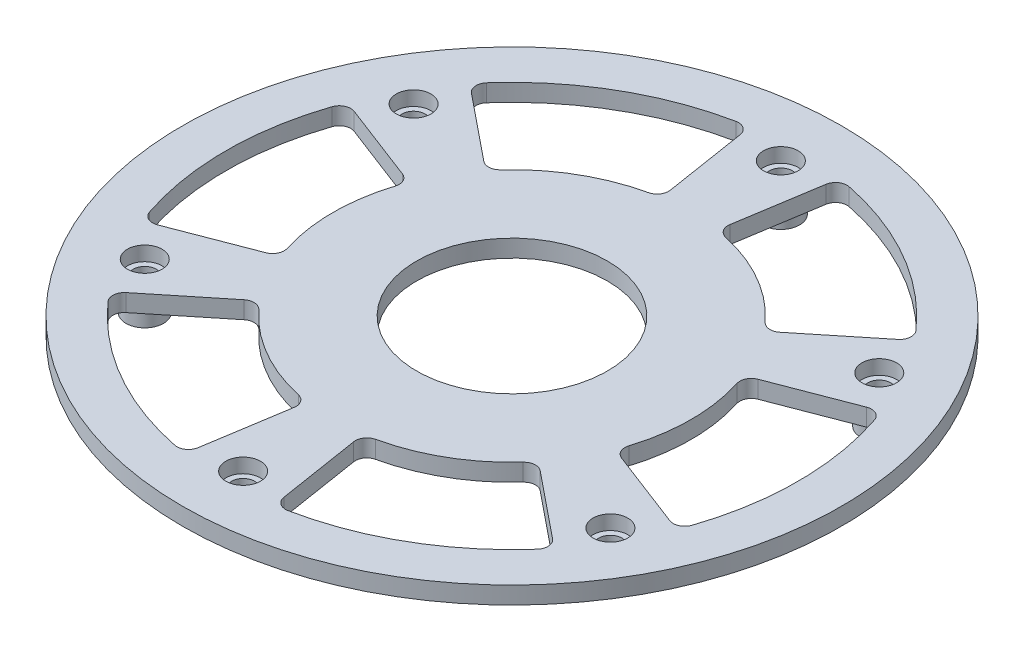
SolidWorks part; units mm, degrees
ref_plane "Front Plane" through (0, 0, 0) normal (0, 0, 1) x (1, 0, 0)
ref_plane "Top Plane" through (0, 0, 0) normal (0, 1, 0) x (1, 0, 0)
ref_plane "Right Plane" through (0, 0, 0) normal (1, 0, 0) x (0, 0, -1)
sketch "Sketch1" plane through (0, 0, 0) normal (0, 1, 0) x (1, 0, 0)
  circle A0 centre (0, 0) radius 57
  dimension "D1" = 114
extrude "Boss-Extrude1" add sketch "Sketch1" along normal blind 3
sketch "Sketch2" plane through (0, 3, 0) normal (0, 1, 0) x (1, 0, 0)
  line L0 (0, 62.5097) -> (0, -64.2706) construction
  circle A0 centre (0, 46.5) radius 2
  dimension "D1" = 4
  dimension "D2" = 46.5
extrude "Cut-Extrude1" cut sketch "Sketch2" against normal through all
pattern_circular "CirPattern1" count 6 over 360 about axis through (0, 0, 0) along (0, 1, 0) of "Cut-Extrude1"
sketch "Sketch5" plane through (0, 0, 0) normal (0, -1, 0) x (1, 0, 0)
  circle A0 centre (0, 46.5) radius 3.25
  circle A1 centre (40.2702, 23.25) radius 3.25
  circle A2 centre (40.2702, -23.25) radius 3.25
  circle A3 centre (0, -46.5) radius 3.25
  circle A4 centre (-40.2702, -23.25) radius 3.25
  circle A5 centre (-40.2702, 23.25) radius 3.25
  dimension "D1" = 6.5
  dimension "D2" = 6.5
extrude "Boss-Extrude2" add sketch "Sketch5" along normal blind 5
sketch "Sketch4" plane through (0, 0, 0) normal (0, -1, 0) x (1, 0, 0)
  circle A0 centre (0, 0) radius 16.5
  dimension "D1" = 33
extrude "Cut-Extrude3" cut sketch "Sketch4" against normal through all
sketch "Sketch8" plane through (0, 3, 0) normal (0, 1, 0) x (1, 0, 0)
  circle A0 centre (-40.2702, -23.25) radius 2 construction
  circle A1 centre (0, -46.5) radius 2 construction
  circle A2 centre (40.2702, -23.25) radius 2 construction
  circle A3 centre (40.2702, 23.25) radius 2 construction
  circle A4 centre (0, 46.5) radius 2 construction
  circle A5 centre (-40.2702, 23.25) radius 2 construction
  circle A6 centre (-40.2702, -23.25) radius 2
  circle A7 centre (0, -46.5) radius 2
  circle A8 centre (40.2702, -23.25) radius 2
  circle A9 centre (40.2702, 23.25) radius 2
  circle A10 centre (0, 46.5) radius 2
  circle A11 centre (-40.2702, 23.25) radius 2
extrude "Cut-Extrude4" cut sketch "Sketch8" against normal through all
sketch "Sketch9" plane through (0, 3, 0) normal (0, 1, 0) x (1, 0, 0)
  circle A0 centre (-40.2702, 23.25) radius 3
  circle A1 centre (0, 46.5) radius 3
  circle A2 centre (40.2702, 23.25) radius 3
  circle A3 centre (40.2702, -23.25) radius 3
  circle A4 centre (0, -46.5) radius 3
  circle A5 centre (-40.2702, -23.25) radius 3
  dimension "D1" = 6
extrude "Cut-Extrude5" cut sketch "Sketch9" against normal blind 2.5
sketch "Sketch10" plane through (0, 3, 0) normal (0, 1, 0) x (1, 0, 0)
  line L0 (0, 0) -> (0, 61.164) construction
  line L1 (0, 0) -> (32.5995, 56.464) construction
  line L2 (4.8495, 30.6183) -> (7.7435, 48.8906)
  line L3 (24.0915, 19.5089) -> (38.4687, 31.1514)
  arc A0 (38.4687, 31.1514) -> (7.7435, 48.8906) centre (0, 0) ccw
  arc A1 (24.0915, 19.5089) -> (4.8495, 30.6183) centre (0, 0) ccw
  dimension "D2" = 99
  dimension "D3" = 62
  dimension "D1" = 30
  dimension "D4" = 21
  dimension "D5" = 21
extrude "Cut-Extrude6" cut sketch "Sketch10" against normal through all
fillet "Fillet1" radius 2 4 edges at (4.8495, 1.5, -30.6183) (24.0915, 1.5, -19.5089) (7.7435, 1.5, -48.8906) (38.4687, 1.5, -31.1514)
pattern_circular "CirPattern2" count 6 over 360 about axis through (0, 0, 0) along (0, 1, 0) of "Fillet1", "Cut-Extrude6"
